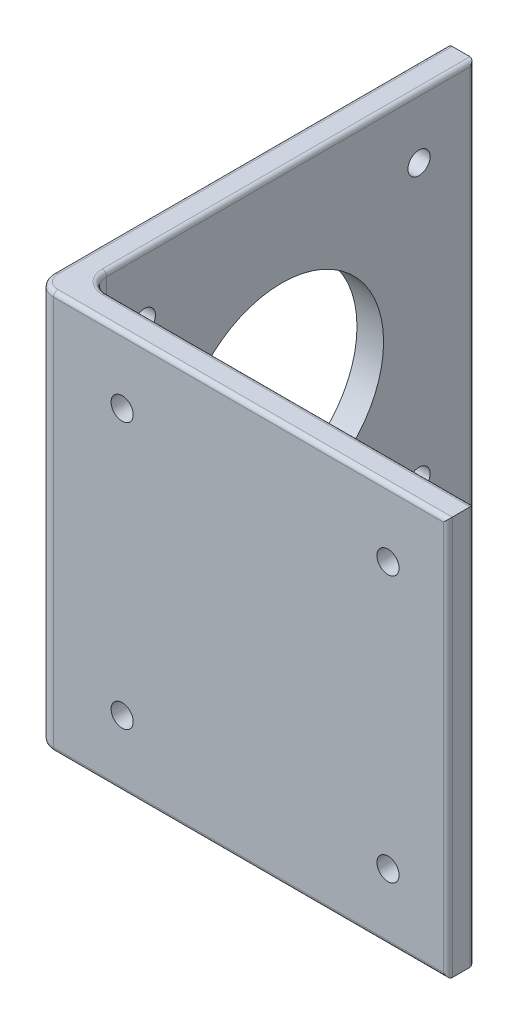
SolidWorks part; units mm, degrees
ref_plane "前视基准面" through (0, 0, 0) normal (0, 0, 1) x (1, 0, 0)
ref_plane "上视基准面" through (0, 0, 0) normal (0, 1, 0) x (1, 0, 0)
ref_plane "右视基准面" through (0, 0, 0) normal (1, 0, 0) x (0, 0, -1)
sketch "草图1" plane through (0, 0, 0) normal (0, 1, 0) x (1, 0, 0)
  line L0 (-22.5, 22.5) -> (22.5, -22.5) construction
  line L2 (-22.5, 22.5) -> (-22.5, -22.5)
  line L3 (-22.5, -22.5) -> (22.5, -22.5)
  point P0 (0, 0)
  point P4 (0, 0)
  dimension "D1" = 45
  dimension "D2" = 45
extrude "拉伸-薄壁1" add sketch "草图1" along normal blind 45 thin thin type mid plane wall 3
sketch "草图2" plane through (-21, 0, 0) normal (1, 0, 0) x (0, 0, -1)
  line L0 (-21, 45) -> (22.5, 0) construction
  line L2 (-14.75, 38) -> (16.25, 38)
  line L3 (-14.75, 38) -> (-14.75, 7)
  line L4 (-14.75, 7) -> (16.25, 7)
  line L5 (16.25, 38) -> (16.25, 7)
  line L6 (-14.75, 38) -> (16.25, 7) construction
  line L7 (-14.75, 7) -> (16.25, 38) construction
  point P4 (0.75, 22.5)
  point P9 (0, 0)
  dimension "D1" = 31
hole_wizard "M3x0.5 螺纹孔1" positions "3D草图1" profile "草图3" tap size "M3x0.5" standard "ANSI Metric" end condition up to next
sketch3d "3D草图1"
  point P0 (-21, 38, 14.75)
  point P3 (-21, 38, -16.25)
  point P6 (-21, 7, -16.25)
  point P9 (-21, 7, 14.75)
sketch "草图3" plane through (-21, 38, 14.75) normal (0, 1, 0) x (0, 0, -1)
  line L0 (0, 0) -> (0, 3)
  line L1 (0, 3) -> (1.25, 3)
  line L2 (1.25, 3) -> (1.25, 0)
  line L5 (1.25, 0) -> (0, 0)
  line L11 (0, -6.35) -> (0, 107.95) construction
  dimension "通孔螺纹孔钻头直径" = 2.5
  dimension "通孔螺纹孔钻头深度" = 3
cosmetic thread "孔螺蚊线1" parameters "D2"=3
cosmetic thread "孔螺蚊线2" parameters "D2"=3
cosmetic thread "孔螺蚊线3" parameters "D2"=3
cosmetic thread "孔螺蚊线4" parameters "D2"=3
sketch "草图4" plane through (0, 0, 21) normal (0, 0, -1) x (-1, 0, 0)
  line L0 (-22.5, 45) -> (21, 0) construction
  line L2 (-15.75, 37.5) -> (14.25, 37.5)
  line L3 (-15.75, 37.5) -> (-15.75, 7.5)
  line L4 (-15.75, 7.5) -> (14.25, 7.5)
  line L5 (14.25, 37.5) -> (14.25, 7.5)
  line L6 (-15.75, 37.5) -> (14.25, 7.5) construction
  line L7 (-15.75, 7.5) -> (14.25, 37.5) construction
  point P4 (-0.75, 22.5)
  dimension "D1" = 30
  dimension "D2" = 30
fillet "圆角1" radius 2 2 edges at (-24, 22.5, 24) (-21, 22.5, 21)
hole_wizard "M3x0.5 螺纹孔2" positions "3D草图2" profile "草图5" tap size "M3x0.5" standard "ANSI Metric" end condition up to next
sketch3d "3D草图2"
  line L1 (-19, 45, 21) -> (-19, 0, 21) construction
  line L2 (-14.25, 37.5, 21) -> (-14.25, 7.5, 21) construction
  point P0 (-14.25, 37.5, 21)
  point P3 (-14.25, 7.5, 21)
  point P6 (15.75, 7.5, 21)
  point P9 (15.75, 37.5, 21)
  dimension "D1" = 4.75
sketch "草图5" plane through (-14.25, 37.5, 21) normal (1, 0, 0) x (0, 1, 0)
  line L0 (0, 0) -> (0, 3)
  line L1 (0, 3) -> (1.25, 3)
  line L2 (1.25, 3) -> (1.25, 0)
  line L5 (1.25, 0) -> (0, 0)
  line L11 (0, -6.35) -> (0, 107.95) construction
  dimension "通孔螺纹孔钻头直径" = 2.5
  dimension "通孔螺纹孔钻头深度" = 3
cosmetic thread "孔螺蚊线5" parameters "D2"=3
cosmetic thread "孔螺蚊线6" parameters "D2"=3
cosmetic thread "孔螺蚊线7" parameters "D2"=3
cosmetic thread "孔螺蚊线8" parameters "D2"=3
fillet "圆角2" radius 0.5 16 edges at (-23.4142, 0, 23.4142) (-20.4142, 45, 20.4142) (-23.4142, 45, 23.4142) (-20.4142, 0, 20.4142) (0.25, 0, 24) (1.75, 0, 21) (-24, 0, -0.25) (0.25, 45, 24) (1.75, 45, 21) (-21, 45, -1.75) (-24, 45, -0.25) (-24, 22.5, -22.5) (-21, 22.5, -22.5) (22.5, 22.5, 21) (22.5, 22.5, 24) (-21, 0, -1.75)
sketch "草图6" plane through (-21, 0, 0) normal (1, 0, 0) x (0, 0, -1)
  circle A0 centre (0.75, 22.5) radius 11.5
  dimension "D1" = 23
extrude "切除-拉伸1" cut sketch "草图6" against normal up to next
